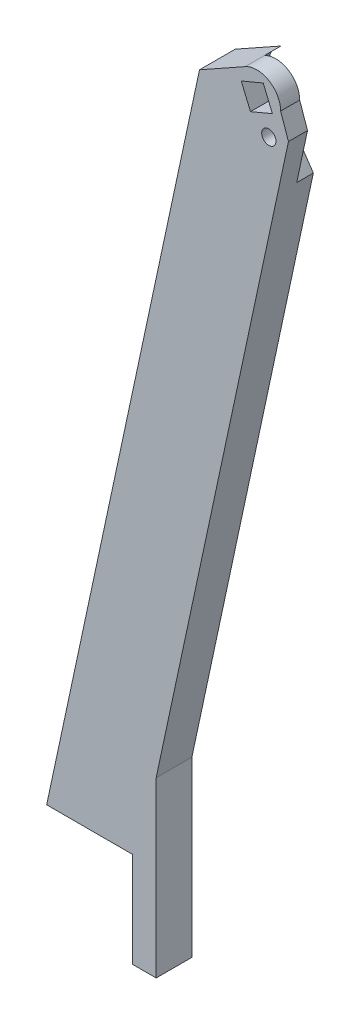
SolidWorks part; units mm, degrees
ref_plane "Front Plane" through (0, 0, 0) normal (0, 0, 1) x (1, 0, 0)
ref_plane "Top Plane" through (0, 0, 0) normal (0, 1, 0) x (1, 0, 0)
ref_plane "Right Plane" through (0, 0, 0) normal (1, 0, 0) x (0, 0, -1)
sketch "Sketch1" plane through (0, 0, 0) normal (0, 0, 1) x (1, 0, 0)
  line L0 (0, 0) -> (0, 25.4)
  line L1 (0, 25.4) -> (-22.86, 25.4)
  line L2 (-22.86, 25.4) -> (17.91, 215.5795)
  line L4 (6.35, 46.2565) -> (6.35, 0)
  line L5 (6.35, 0) -> (0, 0)
  line L8 (-7.7179, -19.366) -> (42.3114, 214.0054) construction
  line L9 (6.35, 46.2565) -> (41.6379, 210.8639)
  line L11 (17.91, 215.5795) -> (30.1005, 222.4026)
  line L12 (41.6379, 210.8639) -> (39.5519, 216.8614)
  arc A0 (39.5519, 216.8614) -> (30.1005, 222.4026) centre (33.2019, 216.8614) ccw
  arc A1 (37.1828, 221.8086) -> (27.9483, 213.2945) centre (33.2019, 216.8614) ccw construction
  arc A2 (37.1828, 221.8086) -> (27.9483, 213.2945) centre (33.2019, 216.8614) ccw construction
  dimension "D1" = 6.35
  dimension "D2" = 22.86
  dimension "D3" = 25.4
  dimension "D4" = 13.97
  dimension "D5" = 6.35
  dimension "D6" = 77.9
  dimension "D7" = 194.5005
extrude "Boss-Extrude1" add sketch "Sketch1" along normal blind 9.525
sketch "Sketch2" plane through (0, 0, 0) normal (0, 0, -1) x (-1, 0, 0)
  line L0 (-41.6379, 210.8639) -> (-39.5519, 216.8614)
  line L1 (-41.6379, 210.8639) -> (-38.7488, 197.387)
  line L2 (-6.35, 46.2565) -> (-41.6379, 210.8639) construction
  line L3 (-27.9483, 213.2945) -> (-81.8075, 133.9679) construction
  line L4 (-38.7488, 197.387) -> (-27.9483, 213.2945)
  arc A0 (-27.9483, 213.2945) -> (-39.5519, 216.8614) centre (-33.2019, 216.8614) ccw
  arc A1 (-30.1005, 222.4026) -> (-39.5519, 216.8614) centre (-33.2019, 216.8614) ccw construction
extrude "Cut-Extrude1" cut sketch "Sketch2" against normal up to surface (4.445 mm away)
sketch "Sketch4" plane through (0, 0, 4.445) normal (0, 0, -1) x (-1, 0, 0)
  line L0 (-29.0448, 218.5586) -> (-31.5047, 212.7044) construction
  line L1 (-34.899, 221.0185) -> (-29.0448, 218.5586) construction
  line L2 (-37.3589, 215.1642) -> (-34.899, 221.0185) construction
  line L3 (-31.5047, 212.7044) -> (-37.3589, 215.1642) construction
  line L4 (-29.0448, 218.5586) -> (-31.5047, 212.7044)
  line L5 (-34.899, 221.0185) -> (-29.0448, 218.5586)
  line L6 (-37.3589, 215.1642) -> (-34.899, 221.0185)
  line L7 (-31.5047, 212.7044) -> (-37.3589, 215.1642)
  circle A1 centre (-36.3996, 209.251) radius 1.905
  dimension "D1" = 3.175
  dimension "D3" = 3.81
  dimension "D2" = 5.08
extrude "Cut-Extrude2" cut sketch "Sketch4" against normal through all
